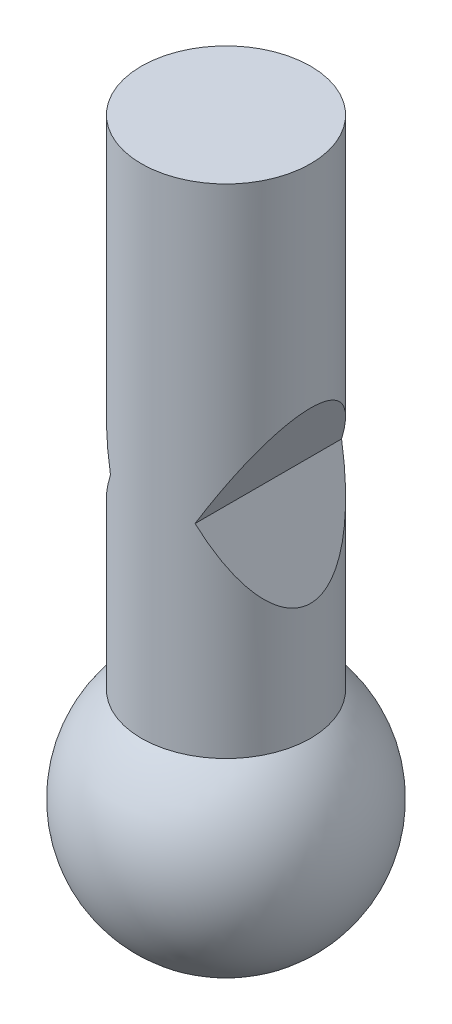
SolidWorks part; units mm, degrees
ref_plane "Front Plane" through (0, 0, 0) normal (0, 0, 1) x (1, 0, 0)
ref_plane "Top Plane" through (0, 0, 0) normal (0, 1, 0) x (1, 0, 0)
ref_plane "Right Plane" through (0, 0, 0) normal (1, 0, 0) x (0, 0, -1)
sketch "Sketch1" plane through (0, 0, 0) normal (0, 0, 1) x (1, 0, 0)
  line L0 (0, -733.1425) -> (0, 35964.5177) construction
  line L1 (0, 15) -> (0, -15)
  arc A0 (0, -15) -> (0, 15) centre (0, 0) ccw
  dimension "D1" = 30
revolve "Revolve1" add sketch "Sketch1" angle 360 about L0
sketch "Sketch2" plane through (0, 0, 0) normal (0, 1, 0) x (1, 0, 0)
  circle A0 centre (0, 0) radius 10
  dimension "D1" = 20
extrude "Boss-Extrude1" add sketch "Sketch2" along normal blind 70
sketch "Sketch3" plane through (0, 0, 0) normal (0, 0, 1) x (1, 0, 0)
  line L0 (10, 45) -> (5, 35)
  line L1 (10, 11.1803) -> (10, 70) construction
  line L2 (5, 35) -> (10, 25)
  line L3 (0, -1000) -> (0, 49000) construction
  line L4 (-1000, 35) -> (49000, 35) construction
  line L5 (10, 45) -> (10, 25)
  line L6 (-10, 45) -> (-10, 25)
  line L7 (-5, 35) -> (-10, 25)
  line L8 (-10, 45) -> (-5, 35)
  arc A1 (-10, 11.1803) -> (10, 11.1803) centre (0, 0) ccw construction
  dimension "D1" = 50
  dimension "D2" = 20
  dimension "D3" = 5
extrude "Cut-Extrude1" cut sketch "Sketch3" against normal through all both and the other way through all
